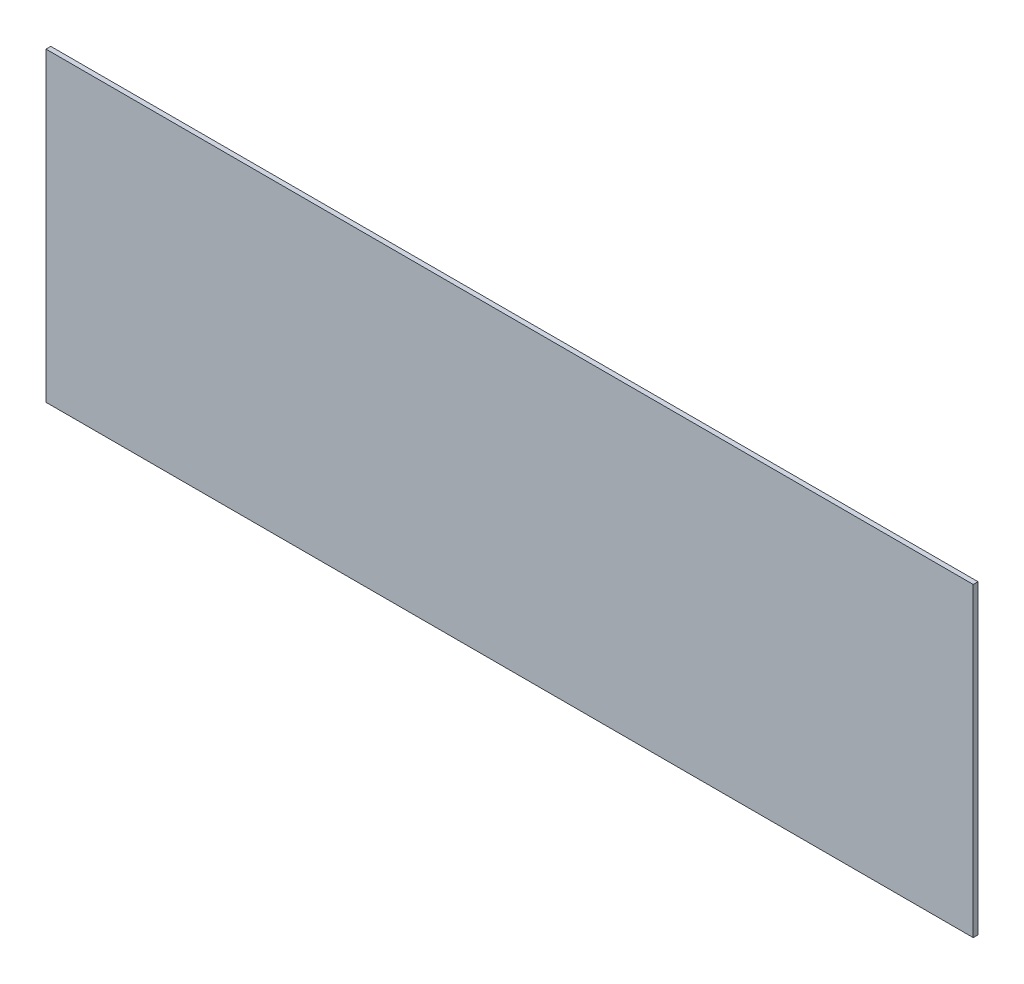
SolidWorks part; units mm, degrees
ref_plane "Front Plane" through (0, 0, 0) normal (0, 0, 1) x (1, 0, 0)
ref_plane "Top Plane" through (0, 0, 0) normal (0, 1, 0) x (1, 0, 0)
ref_plane "Right Plane" through (0, 0, 0) normal (1, 0, 0) x (0, 0, -1)
sketch "Sketch1" plane through (0, 0, 0) normal (0, 0, 1) x (1, 0, 0)
  line L1 (-307.975, -101.6) -> (307.975, -101.6)
  line L2 (-307.975, -101.6) -> (-307.975, 101.6)
  line L3 (-307.975, 101.6) -> (307.975, 101.6)
  line L4 (307.975, -101.6) -> (307.975, 101.6)
  line L5 (-307.975, -101.6) -> (307.975, 101.6) construction
  line L6 (-307.975, 101.6) -> (307.975, -101.6) construction
  point P0 (0, 0)
  dimension "D1" = 203.2
  dimension "D2" = 615.95
extrude "Boss-Extrude1" add sketch "Sketch1" along normal blind 3.175
